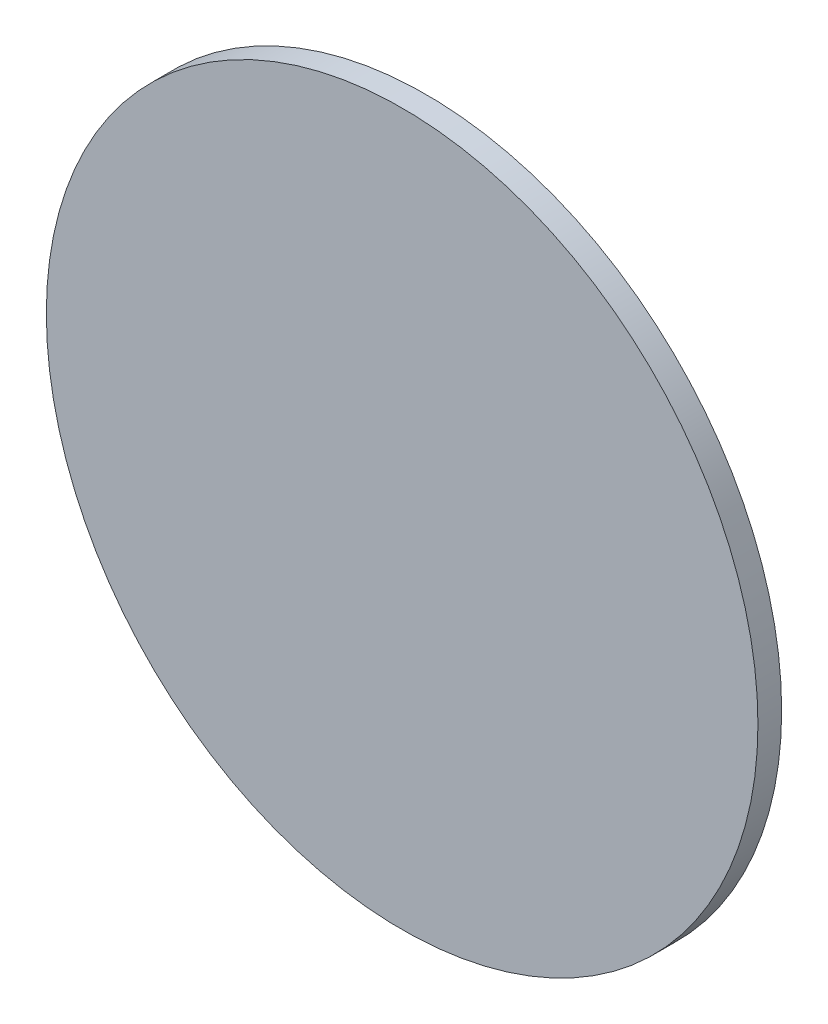
SolidWorks part; units mm, degrees
ref_plane "Front Plane" through (0, 0, 0) normal (0, 0, 1) x (1, 0, 0)
ref_plane "Top Plane" through (0, 0, 0) normal (0, 1, 0) x (1, 0, 0)
ref_plane "Right Plane" through (0, 0, 0) normal (1, 0, 0) x (0, 0, -1)
sketch "Sketch1" plane through (0, 0, 0) normal (0, 0, 1) x (1, 0, 0)
  circle A0 centre (0, 0) radius 60
  dimension "D1" = 120
extrude "Boss-Extrude1" add sketch "Sketch1" along normal blind 4
ref_plane "Plane1" through (0, 0, 0.6) normal (0, 0, -1) x (-1, 0, 0)
sketch "Sketch2" plane through (0, 0, 0.6) normal (0, 0, -1) x (-1, 0, 0)
  circle A0 centre (0, 0) radius 20 construction
  circle A1 centre (0, 20) radius 2.7
  circle A2 centre (20, 0) radius 2.7
  circle A3 centre (0, -20) radius 2.7
  circle A4 centre (-20, 0) radius 2.7
  dimension "D1" = 5.4
  dimension "D2" = 5.4
  dimension "D3" = 5.4
  dimension "D4" = 5.4
extrude "Cut-Extrude1" cut sketch "Sketch2" against normal blind 2.5
